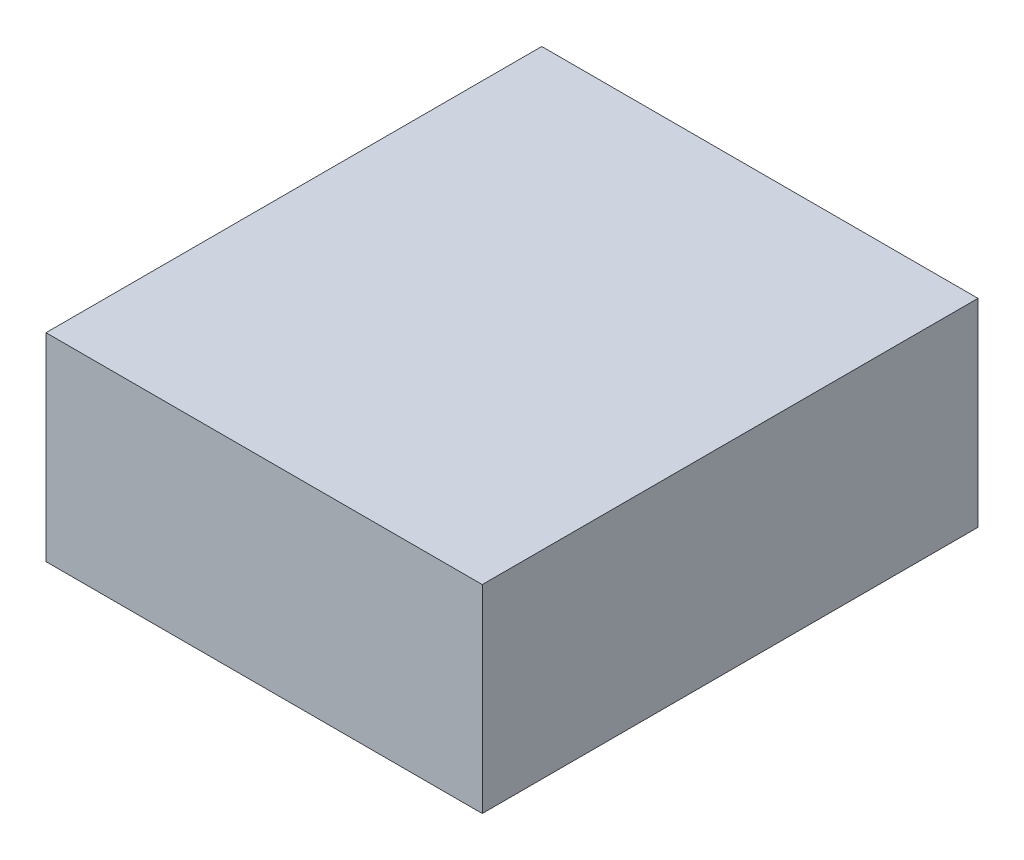
SolidWorks part; units mm, degrees
ref_plane "Front Plane" through (0, 0, 0) normal (0, 0, 1) x (1, 0, 0)
ref_plane "Top Plane" through (0, 0, 0) normal (0, 1, 0) x (1, 0, 0)
ref_plane "Right Plane" through (0, 0, 0) normal (1, 0, 0) x (0, 0, -1)
sketch "Sketch1" plane through (0, 0, 0) normal (0, 1, 0) x (1, 0, 0)
  line L1 (-110, -125) -> (110, -125)
  line L2 (-110, -125) -> (-110, 125)
  line L3 (-110, 125) -> (110, 125)
  line L4 (110, -125) -> (110, 125)
  line L5 (-110, -125) -> (110, 125) construction
  line L6 (-110, 125) -> (110, -125) construction
  point P0 (0, 0)
  dimension "D1" = 220
  dimension "D2" = 250
extrude "Boss-Extrude1" add sketch "Sketch1" along normal blind 100
